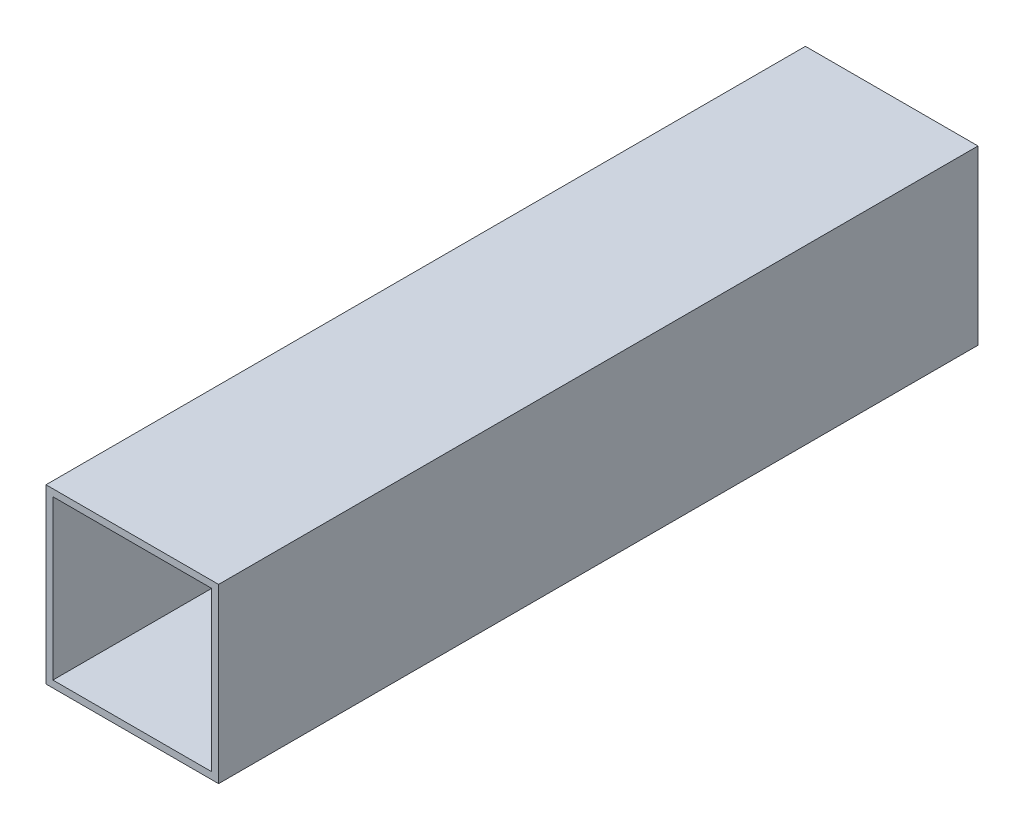
SolidWorks part; units mm, degrees
ref_plane "Front Plane" through (0, 0, 0) normal (0, 0, 1) x (1, 0, 0)
ref_plane "Top Plane" through (0, 0, 0) normal (0, 1, 0) x (1, 0, 0)
ref_plane "Right Plane" through (0, 0, 0) normal (1, 0, 0) x (0, 0, -1)
sketch "Sketch1" plane through (0, 0, 0) normal (0, 0, 1) x (1, 0, 0)
  line L1 (-25, -25) -> (25, -25)
  line L2 (-25, -25) -> (-25, 25)
  line L3 (-25, 25) -> (25, 25)
  line L4 (25, -25) -> (25, 25)
  line L5 (-25, -25) -> (25, 25) construction
  line L6 (-25, 25) -> (25, -25) construction
  line L7 (-23, -23) -> (23, -23)
  line L8 (-23, -23) -> (-23, 23)
  line L9 (-23, 23) -> (23, 23)
  line L10 (23, -23) -> (23, 23)
  line L11 (-23, -23) -> (23, 23) construction
  line L12 (-23, 23) -> (23, -23) construction
  point P0 (0, 0)
  point P6 (0, 0)
  dimension "D1" = 50
  dimension "D2" = 46
extrude "Boss-Extrude1" add sketch "Sketch1" along normal blind 220
